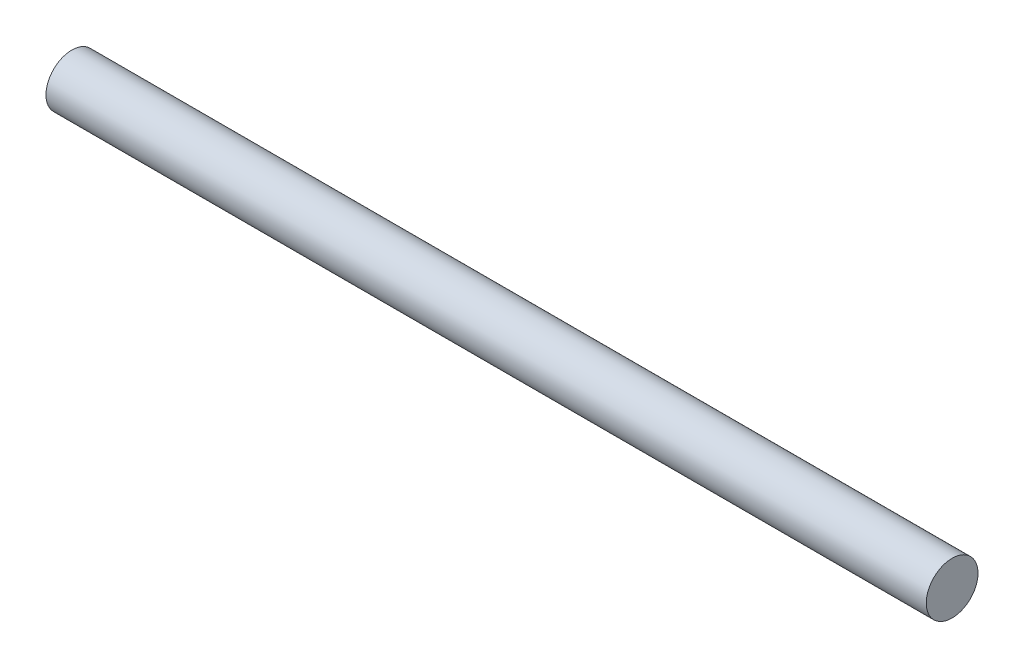
SolidWorks part; units mm, degrees
material "201 Acero inoxidable recocido (SS)"
ref_plane "Alzado" through (0, 0, 0) normal (0, 0, 1) x (1, 0, 0)
ref_plane "Planta" through (0, 0, 0) normal (0, 1, 0) x (1, 0, 0)
ref_plane "Vista lateral" through (0, 0, 0) normal (1, 0, 0) x (0, 0, -1)
sketch "Croquis1" plane through (0, 0, 0) normal (1, 0, 0) x (0, 0, -1)
  circle A0 centre (0, 0) radius 10
  dimension "D1" = 20
extrude "Saliente-Extruir1" add sketch "Croquis1" along normal blind 340
